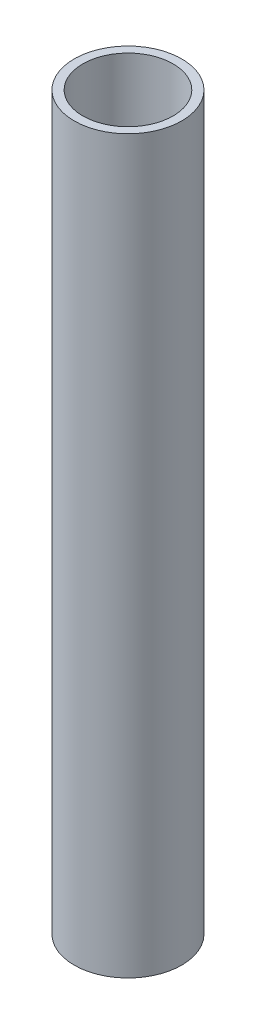
SolidWorks part; units mm, degrees
ref_plane "Alzado" through (0, 0, 0) normal (0, 0, 1) x (1, 0, 0)
ref_plane "Planta" through (0, 0, 0) normal (0, 1, 0) x (1, 0, 0)
ref_plane "Vista lateral" through (0, 0, 0) normal (1, 0, 0) x (0, 0, -1)
sketch "Croquis1" plane through (0, 0, 0) normal (0, 1, 0) x (1, 0, 0)
  circle A0 centre (0, 0) radius 12.5
  circle A1 centre (0, 0) radius 10.5
  dimension "D1" = 25
  dimension "D2" = 2
extrude "Saliente-Extruir1" add sketch "Croquis1" along normal blind 170
